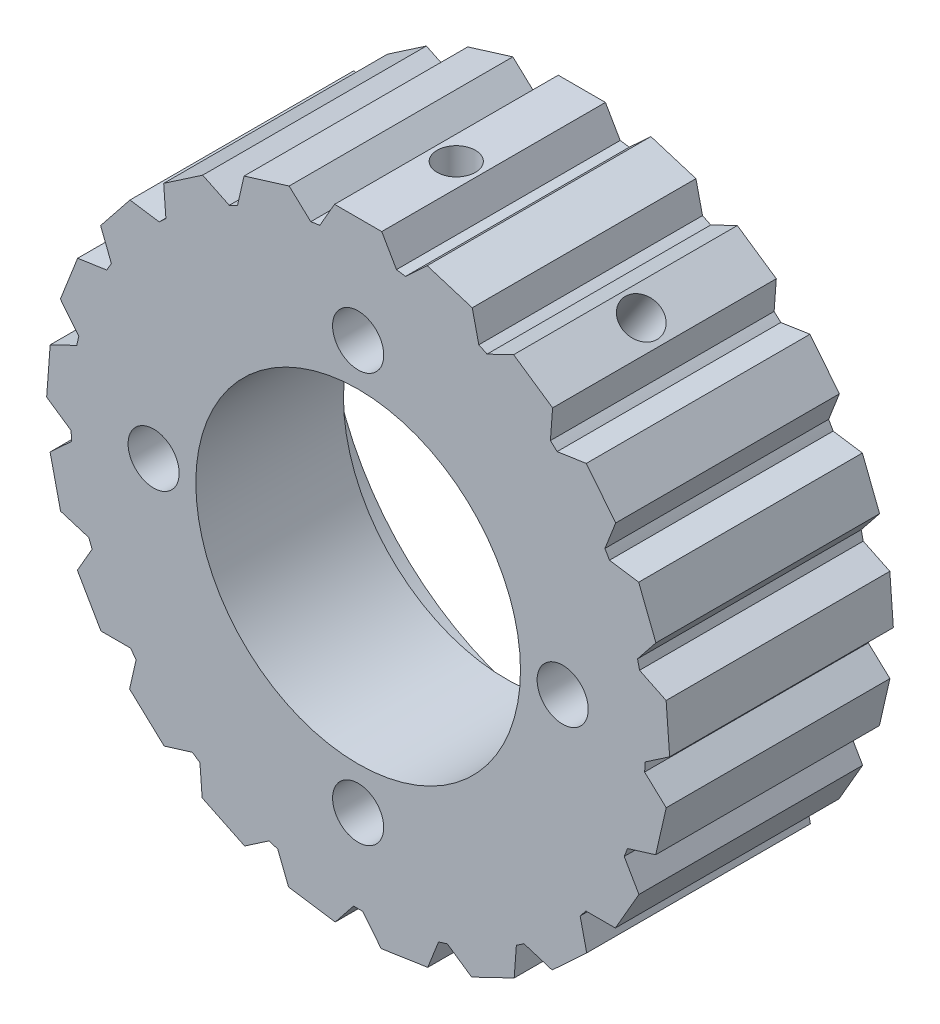
SolidWorks part; units mm, degrees
material "PBT General Purpose"
ref_plane "Front Plane" through (0, 0, 0) normal (0, 0, 1) x (1, 0, 0)
ref_plane "Top Plane" through (0, 0, 0) normal (0, 1, 0) x (1, 0, 0)
ref_plane "Right Plane" through (0, 0, 0) normal (1, 0, 0) x (0, 0, -1)
sketch "Sketch1" plane through (0, 0, 0) normal (0, 0, 1) x (1, 0, 0)
  line L1 (-3, 22.2991) -> (-1.8453, 24.2991)
  line L2 (-1.8453, 24.2991) -> (1.8453, 24.2991)
  line L3 (1.8453, 24.2991) -> (3, 22.2991)
  circle A0 centre (0, 0) radius 22.5
  circle A1 centre (0, 0) radius 12.7
  dimension "D1" = 45
  dimension "D2" = 25.4
  dimension "D3" = 3
  dimension "D4" = 120
  dimension "D5" = 120
  dimension "D6" = 3
  dimension "D7" = 2
extrude "Boss-Extrude1" add sketch "Sketch1" along normal blind 17.5
sketch "Sketch2" plane through (0, 0, 17.5) normal (0, 0, 1) x (1, 0, 0)
  circle A0 centre (-11.6, 11.6) radius 1.75
  dimension "D1" = 3.5
  dimension "D2" = 11.6
  dimension "D3" = 11.6
extrude "Cut-Extrude1" cut sketch "Sketch2" against normal blind 10
pattern_circular "CirPattern1" count 4 over 360 about axis through (0, 0, 0) along (0, 0, 1) of "Cut-Extrude1"
pattern_circular "CirPattern7" count 21 over 360 about axis through (0, 0, 0) along (0, 0, 1) of "Boss-Extrude1"
sketch "Sketch5" plane through (0, 0, 0) normal (0, 0, -1) x (-1, 0, 0)
  line L63 (3, 22.2991) -> (1.8453, 24.2991)
  line L64 (1.8453, 24.2991) -> (-1.8453, 24.2991)
  line L65 (-1.8453, 24.2991) -> (-3, 22.2991)
  line L66 (-3.7061, 22.1927) -> (-5.399, 23.7635)
  line L67 (-3.7061, 22.1927) -> (-5.399, 23.7635)
  line L68 (-5.399, 23.7635) -> (-8.9256, 22.6757)
  line L69 (-5.399, 23.7635) -> (-8.9256, 22.6757)
  line L70 (-8.9256, 22.6757) -> (-9.4395, 20.4242)
  line L71 (-8.9256, 22.6757) -> (-9.4395, 20.4242)
  line L72 (-10.0828, 20.1143) -> (-12.1635, 21.1164)
  line L73 (-10.0828, 20.1143) -> (-12.1635, 21.1164)
  line L74 (-12.1635, 21.1164) -> (-15.2128, 19.0374)
  line L75 (-12.1635, 21.1164) -> (-15.2128, 19.0374)
  line L76 (-15.2128, 19.0374) -> (-15.0402, 16.7344)
  line L77 (-15.2128, 19.0374) -> (-15.0402, 16.7344)
  line L78 (-15.5637, 16.2488) -> (-17.8473, 16.593)
  line L79 (-15.5637, 16.2488) -> (-17.8473, 16.593)
  line L80 (-17.8473, 16.593) -> (-20.1483, 13.7075)
  line L81 (-17.8473, 16.593) -> (-20.1483, 13.7075)
  line L82 (-20.1483, 13.7075) -> (-19.3046, 11.5578)
  line L83 (-20.1483, 13.7075) -> (-19.3046, 11.5578)
  line L84 (-20.8116, -8.5515) -> (-21.9663, -10.5515)
  line L85 (-21.9663, -10.5515) -> (-20.121, -13.7476)
  line L86 (-20.121, -13.7476) -> (-17.8116, -13.7476)
  line L87 (-17.3664, -14.3059) -> (-17.8803, -16.5574)
  line L88 (-17.8803, -16.5574) -> (-15.1749, -19.0676)
  line L89 (-15.1749, -19.0676) -> (-12.9681, -18.3869)
  line L90 (-12.3781, -18.7891) -> (-12.2055, -21.0921)
  line L91 (-12.2055, -21.0921) -> (-8.8804, -22.6934)
  line L92 (-8.8804, -22.6934) -> (-6.9723, -21.3924)
  line L93 (-6.29, -21.6029) -> (-5.4463, -23.7527)
  line L94 (-5.4463, -23.7527) -> (-1.7969, -24.3027)
  line L95 (-1.7969, -24.3027) -> (-0.357, -22.4972)
  line L96 (0.357, -22.4972) -> (1.7969, -24.3027)
  line L97 (1.7969, -24.3027) -> (5.4463, -23.7527)
  line L98 (5.4463, -23.7527) -> (6.29, -21.6029)
  line L99 (6.9723, -21.3924) -> (8.8804, -22.6934)
  line L100 (8.8804, -22.6934) -> (12.2055, -21.0921)
  line L101 (12.2055, -21.0921) -> (12.3781, -18.7891)
  line L102 (12.9681, -18.3869) -> (15.1749, -19.0676)
  line L103 (15.1749, -19.0676) -> (17.8803, -16.5574)
  line L104 (17.8803, -16.5574) -> (17.3664, -14.3059)
  line L105 (17.8116, -13.7476) -> (20.121, -13.7476)
  line L106 (20.121, -13.7476) -> (21.9663, -10.5515)
  line L107 (21.9663, -10.5515) -> (20.8116, -8.5515)
  line L108 (21.0725, -7.8868) -> (23.2793, -7.2061)
  line L109 (23.2793, -7.2061) -> (24.1005, -3.608)
  line L110 (24.1005, -3.608) -> (22.4076, -2.0372)
  line L111 (22.4609, -1.3252) -> (24.3691, -0.0243)
  line L112 (24.3691, -0.0243) -> (24.0933, 3.656)
  line L113 (24.0933, 3.656) -> (22.0126, 4.658)
  line L114 (21.8537, 5.3542) -> (23.2936, 7.1597)
  line L115 (23.2936, 7.1597) -> (21.9452, 10.5952)
  line L116 (21.9452, 10.5952) -> (19.6616, 10.9394)
  line L117 (19.3046, 11.5578) -> (20.1483, 13.7075)
  line L118 (20.1483, 13.7075) -> (17.8473, 16.593)
  line L119 (17.8473, 16.593) -> (15.5637, 16.2488)
  line L120 (15.0402, 16.7344) -> (15.2128, 19.0374)
  line L121 (15.2128, 19.0374) -> (12.1635, 21.1164)
  line L122 (12.1635, 21.1164) -> (10.0828, 20.1143)
  line L123 (9.4395, 20.4242) -> (8.9256, 22.6757)
  line L124 (8.9256, 22.6757) -> (5.399, 23.7635)
  line L125 (5.399, 23.7635) -> (3.7061, 22.1927)
  line L126 (3, 22.2991) -> (1.8453, 24.2991)
  line L127 (1.8453, 24.2991) -> (-1.8453, 24.2991)
  line L128 (-1.8453, 24.2991) -> (-3, 22.2991)
  line L147 (-20.8116, -8.5515) -> (-21.9663, -10.5515)
  line L148 (-21.9663, -10.5515) -> (-20.121, -13.7476)
  line L149 (-20.121, -13.7476) -> (-17.8116, -13.7476)
  line L150 (-17.3664, -14.3059) -> (-17.8803, -16.5574)
  line L151 (-17.8803, -16.5574) -> (-15.1749, -19.0676)
  line L152 (-15.1749, -19.0676) -> (-12.9681, -18.3869)
  line L153 (-12.3781, -18.7891) -> (-12.2055, -21.0921)
  line L154 (-12.2055, -21.0921) -> (-8.8804, -22.6934)
  line L155 (-8.8804, -22.6934) -> (-6.9723, -21.3924)
  line L156 (-6.29, -21.6029) -> (-5.4463, -23.7527)
  line L157 (-5.4463, -23.7527) -> (-1.7969, -24.3027)
  line L158 (-1.7969, -24.3027) -> (-0.357, -22.4972)
  line L159 (0.357, -22.4972) -> (1.7969, -24.3027)
  line L160 (1.7969, -24.3027) -> (5.4463, -23.7527)
  line L161 (5.4463, -23.7527) -> (6.29, -21.6029)
  line L162 (6.9723, -21.3924) -> (8.8804, -22.6934)
  line L163 (8.8804, -22.6934) -> (12.2055, -21.0921)
  line L164 (12.2055, -21.0921) -> (12.3781, -18.7891)
  line L165 (12.9681, -18.3869) -> (15.1749, -19.0676)
  line L166 (15.1749, -19.0676) -> (17.8803, -16.5574)
  line L167 (17.8803, -16.5574) -> (17.3664, -14.3059)
  line L168 (17.8116, -13.7476) -> (20.121, -13.7476)
  line L169 (20.121, -13.7476) -> (21.9663, -10.5515)
  line L170 (21.9663, -10.5515) -> (20.8116, -8.5515)
  line L171 (21.0725, -7.8868) -> (23.2793, -7.2061)
  line L172 (23.2793, -7.2061) -> (24.1005, -3.608)
  line L173 (24.1005, -3.608) -> (22.4076, -2.0372)
  line L174 (22.4609, -1.3252) -> (24.3691, -0.0243)
  line L175 (24.3691, -0.0243) -> (24.0933, 3.656)
  line L176 (24.0933, 3.656) -> (22.0126, 4.658)
  line L177 (21.8537, 5.3542) -> (23.2936, 7.1597)
  line L178 (23.2936, 7.1597) -> (21.9452, 10.5952)
  line L179 (21.9452, 10.5952) -> (19.6616, 10.9394)
  line L180 (19.3046, 11.5578) -> (20.1483, 13.7075)
  line L181 (20.1483, 13.7075) -> (17.8473, 16.593)
  line L182 (17.8473, 16.593) -> (15.5637, 16.2488)
  line L183 (15.0402, 16.7344) -> (15.2128, 19.0374)
  line L184 (15.2128, 19.0374) -> (12.1635, 21.1164)
  line L185 (12.1635, 21.1164) -> (10.0828, 20.1143)
  line L186 (9.4395, 20.4242) -> (8.9256, 22.6757)
  line L187 (8.9256, 22.6757) -> (5.399, 23.7635)
  line L188 (5.399, 23.7635) -> (3.7061, 22.1927)
  line L189 (-19.6616, 10.9394) -> (-21.9452, 10.5952)
  line L190 (-19.6616, 10.9394) -> (-21.9452, 10.5952)
  line L191 (-21.9452, 10.5952) -> (-23.2936, 7.1597)
  line L192 (-21.9452, 10.5952) -> (-23.2936, 7.1597)
  line L193 (-23.2936, 7.1597) -> (-21.8537, 5.3542)
  line L194 (-23.2936, 7.1597) -> (-21.8537, 5.3542)
  line L195 (-22.0126, 4.658) -> (-24.0933, 3.656)
  line L196 (-22.0126, 4.658) -> (-24.0933, 3.656)
  line L197 (-24.0933, 3.656) -> (-24.3691, -0.0243)
  line L198 (-24.0933, 3.656) -> (-24.3691, -0.0243)
  line L199 (-24.3691, -0.0243) -> (-22.4609, -1.3252)
  line L200 (-24.3691, -0.0243) -> (-22.4609, -1.3252)
  line L201 (-22.4076, -2.0372) -> (-24.1005, -3.608)
  line L202 (-22.4076, -2.0372) -> (-24.1005, -3.608)
  line L203 (-24.1005, -3.608) -> (-23.2793, -7.2061)
  line L204 (-24.1005, -3.608) -> (-23.2793, -7.2061)
  line L205 (-23.2793, -7.2061) -> (-21.0725, -7.8868)
  line L206 (-23.2793, -7.2061) -> (-21.0725, -7.8868)
  circle A0 centre (0, 0) radius 19.8438
  arc A16 (3.7061, 22.1927) -> (3, 22.2991) centre (0, 0) ccw
  arc A17 (3.7061, 22.1927) -> (3, 22.2991) centre (0, 0) ccw
  arc A18 (-3, 22.2991) -> (-3.7061, 22.1927) centre (0, 0) ccw
  arc A19 (-3, 22.2991) -> (-3.7061, 22.1927) centre (0, 0) ccw
  arc A20 (-17.8116, -13.7476) -> (-17.3664, -14.3059) centre (0, 0) ccw
  arc A21 (-17.8116, -13.7476) -> (-17.3664, -14.3059) centre (0, 0) ccw
  arc A22 (-12.9681, -18.3869) -> (-12.3781, -18.7891) centre (0, 0) ccw
  arc A23 (-12.9681, -18.3869) -> (-12.3781, -18.7891) centre (0, 0) ccw
  arc A24 (-6.9723, -21.3924) -> (-6.29, -21.6029) centre (0, 0) ccw
  arc A25 (-6.9723, -21.3924) -> (-6.29, -21.6029) centre (0, 0) ccw
  arc A26 (-0.357, -22.4972) -> (0.357, -22.4972) centre (0, 0) ccw
  arc A27 (-0.357, -22.4972) -> (0.357, -22.4972) centre (0, 0) ccw
  arc A28 (6.29, -21.6029) -> (6.9723, -21.3924) centre (0, 0) ccw
  arc A29 (6.29, -21.6029) -> (6.9723, -21.3924) centre (0, 0) ccw
  arc A30 (12.3781, -18.7891) -> (12.9681, -18.3869) centre (0, 0) ccw
  arc A31 (12.3781, -18.7891) -> (12.9681, -18.3869) centre (0, 0) ccw
  arc A32 (17.3664, -14.3059) -> (17.8116, -13.7476) centre (0, 0) ccw
  arc A33 (17.3664, -14.3059) -> (17.8116, -13.7476) centre (0, 0) ccw
  arc A34 (20.8116, -8.5515) -> (21.0725, -7.8868) centre (0, 0) ccw
  arc A35 (20.8116, -8.5515) -> (21.0725, -7.8868) centre (0, 0) ccw
  arc A36 (22.4076, -2.0372) -> (22.4609, -1.3252) centre (0, 0) ccw
  arc A37 (22.4076, -2.0372) -> (22.4609, -1.3252) centre (0, 0) ccw
  arc A38 (22.0126, 4.658) -> (21.8537, 5.3542) centre (0, 0) ccw
  arc A39 (22.0126, 4.658) -> (21.8537, 5.3542) centre (0, 0) ccw
  arc A40 (19.6616, 10.9394) -> (19.3046, 11.5578) centre (0, 0) ccw
  arc A41 (19.6616, 10.9394) -> (19.3046, 11.5578) centre (0, 0) ccw
  arc A63 (15.5637, 16.2488) -> (15.0402, 16.7344) centre (0, 0) ccw
  arc A64 (15.5637, 16.2488) -> (15.0402, 16.7344) centre (0, 0) ccw
  arc A65 (10.0828, 20.1143) -> (9.4395, 20.4242) centre (0, 0) ccw
  arc A66 (10.0828, 20.1143) -> (9.4395, 20.4242) centre (0, 0) ccw
  arc A73 (-9.4395, 20.4242) -> (-10.0828, 20.1143) centre (0, 0) ccw
  arc A74 (-9.4395, 20.4242) -> (-10.0828, 20.1143) centre (0, 0) ccw
  arc A75 (-15.0402, 16.7344) -> (-15.5637, 16.2488) centre (0, 0) ccw
  arc A76 (-15.0402, 16.7344) -> (-15.5637, 16.2488) centre (0, 0) ccw
  arc A77 (-19.3046, 11.5578) -> (-19.6616, 10.9394) centre (0, 0) ccw
  arc A78 (-19.3046, 11.5578) -> (-19.6616, 10.9394) centre (0, 0) ccw
  arc A79 (-21.8537, 5.3542) -> (-22.0126, 4.658) centre (0, 0) ccw
  arc A80 (-21.8537, 5.3542) -> (-22.0126, 4.658) centre (0, 0) ccw
  arc A81 (-22.4609, -1.3252) -> (-22.4076, -2.0372) centre (0, 0) ccw
  arc A82 (-22.4609, -1.3252) -> (-22.4076, -2.0372) centre (0, 0) ccw
  arc A83 (-21.0725, -7.8868) -> (-20.8116, -8.5515) centre (0, 0) ccw
  arc A84 (-21.0725, -7.8868) -> (-20.8116, -8.5515) centre (0, 0) ccw
  dimension "D2" = 39.6875
  dimension "D1" = 0
extrude "Cut-Extrude5" cut sketch "Sketch5" against normal blind 5.95 contours A0
sketch "Sketch9" plane through (0, 0, 5.95) normal (0, 0, -1) x (-1, 0, 0)
  circle A0 centre (0, 16) radius 2
  dimension "D1" = 4
extrude "Cut-Extrude11" cut sketch "Sketch9" against normal blind 26
pattern_circular "CirPattern9" count 4 over 360 about axis through (0, 0, 0) along (0, 0, 1) of "Cut-Extrude11"
sketch "Sketch10" plane through (13.6882, 20.0769, 0) normal (0.5633, 0.8262, 0) x (0.8262, -0.5633, 0)
  circle A0 centre (-0.0481, -8.9999) radius 1.5
  dimension "D2" = 3
  dimension "D3" = 1.845
  dimension "D1" = 9
extrude "Cut-Extrude12" cut sketch "Sketch10" against normal blind 26
sketch "Sketch11" plane through (0, 24.2991, 0) normal (0, 1, 0) x (1, 0, 0)
  circle A0 centre (0, -9.8261) radius 1.5
  dimension "D1" = 3
extrude "Cut-Extrude13" cut sketch "Sketch11" against normal blind 30
